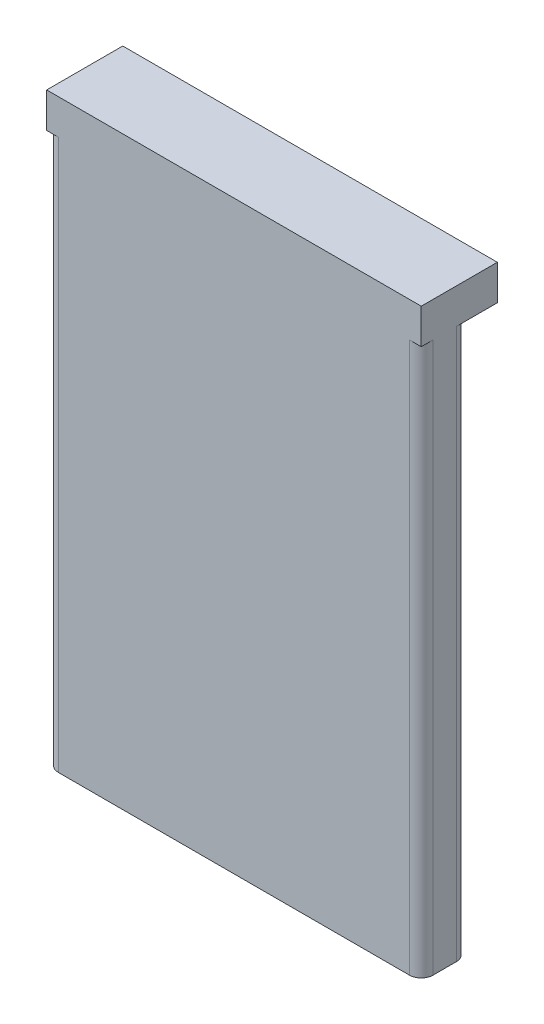
SolidWorks part; units mm, degrees
ref_plane "Front Plane" through (0, 0, 0) normal (0, 0, 1) x (1, 0, 0)
ref_plane "Top Plane" through (0, 0, 0) normal (0, 1, 0) x (1, 0, 0)
ref_plane "Right Plane" through (0, 0, 0) normal (1, 0, 0) x (0, 0, -1)
sketch "Sketch1" plane through (0, 0, 0) normal (0, 0, 1) x (1, 0, 0)
  line L0 (-16, 0) -> (16, 0)
  line L1 (16, 0) -> (16, 50)
  line L3 (-16, 50) -> (-16, 0)
  line L7 (16, 50) -> (-16, 50)
  dimension "D1" = 50
  dimension "D3" = 32
extrude "Extrude1" add sketch "Sketch1" along normal blind 4
fillet "Fillet1" radius 1 4 edges at (-16, 25, 0) (16, 25, 0) (16, 25, 4) (-16, 25, 4)
sketch "Sketch3" plane through (0, 50, 0) normal (0, 1, 0) x (1, 0, 0)
  line L1 (-16, -4) -> (16, -4)
  line L2 (-16, -4) -> (-16, 2.5)
  line L3 (-16, 2.5) -> (16, 2.5)
  line L4 (16, -4) -> (16, 2.5)
  dimension "D1" = 6.5
extrude "Extrude3" add sketch "Sketch3" against normal blind 3
